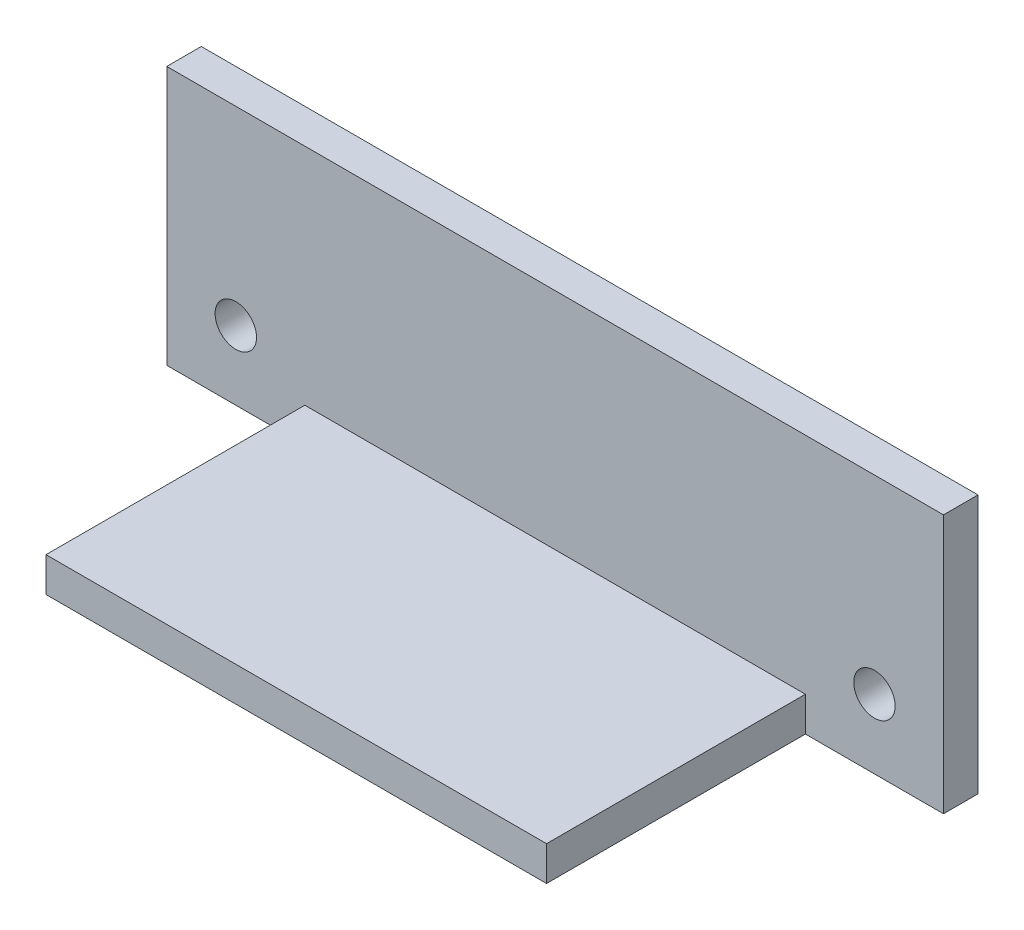
SolidWorks part; units mm, degrees
ref_plane "Front Plane" through (0, 0, 0) normal (0, 0, 1) x (1, 0, 0)
ref_plane "Top Plane" through (0, 0, 0) normal (0, 1, 0) x (1, 0, 0)
ref_plane "Right Plane" through (0, 0, 0) normal (1, 0, 0) x (0, 0, -1)
sketch "Sketch2" plane through (0, 0, 0) normal (0, 1, 0) x (1, 0, 0)
  line L0 (-38.8972, 0) -> (-9.8972, 0)
  line L1 (-38.8972, 0) -> (-38.8972, -15.11)
  line L2 (-38.8972, -15.11) -> (-9.8972, -15.11)
  line L3 (-9.8972, -15.11) -> (-9.8972, 0)
  dimension "D1" = 15.11
  dimension "D2" = 29
extrude "Boss-Extrude1" add sketch "Sketch2" along normal blind 2
sketch "Sketch7" plane through (0, 0, 0) normal (0, -1, 0) x (-1, 0, 0)
  line L0 (1.8972, -0.1133) -> (46.8972, -0.1133)
  line L1 (1.8972, -0.1133) -> (1.8972, 1.8867)
  line L2 (46.8972, -0.1133) -> (46.8972, 1.8867)
  line L3 (1.8972, 1.8867) -> (46.8972, 1.8867)
  dimension "D1" = 45
  dimension "D2" = 8
extrude "Boss-Extrude2" add sketch "Sketch7" against normal blind 15 contours L1 L3 L2 L0
hole_wizard "M2 Clearance Hole1" positions "Sketch8" profile "Sketch9" hole size "M2" standard "ANSI Metric" end condition through all
sketch "Sketch8" plane through (0, 0, 0.1133) normal (0, 0, 1) x (1, 0, 0)
  line L0 (-46.8972, 15) -> (-46.8972, 0) construction
  line L1 (-38.8972, 0) -> (-46.8972, 0) construction
  point P0 (-42.8972, 4)
  dimension "D1" = 4
  dimension "D2" = 4
sketch "Sketch9" plane through (-42.8972, 4, 0.1133) normal (1, 0, 0) x (0, -1, 0)
  line L0 (0, 0) -> (0, 2)
  line L1 (0, 2) -> (1.2, 2)
  line L2 (1.2, 2) -> (1.2, 0)
  line L5 (1.2, 0) -> (0, 0)
  line L11 (0, -6.35) -> (0, 107.95) construction
  dimension "Thru Hole Dia." = 2.4
  dimension "Thru Hole Depth" = 2
hole_wizard "M2 Clearance Hole2" positions "Sketch10" profile "Sketch11" hole size "M2" standard "ANSI Metric" end condition through all
sketch "Sketch10" plane through (0, 0, 0.1133) normal (0, 0, 1) x (1, 0, 0)
  line L0 (-1.8972, 15) -> (-1.8972, 0) construction
  line L1 (-1.8972, 0) -> (-9.8972, 0) construction
  point P0 (-5.8972, 4)
  dimension "D1" = 4
  dimension "D2" = 4
sketch "Sketch11" plane through (-5.8972, 4, 0.1133) normal (1, 0, 0) x (0, -1, 0)
  line L0 (0, 0) -> (0, 2)
  line L1 (0, 2) -> (1.2, 2)
  line L2 (1.2, 2) -> (1.2, 0)
  line L5 (1.2, 0) -> (0, 0)
  line L11 (0, -6.35) -> (0, 107.95) construction
  dimension "Thru Hole Dia." = 2.4
  dimension "Thru Hole Depth" = 2
